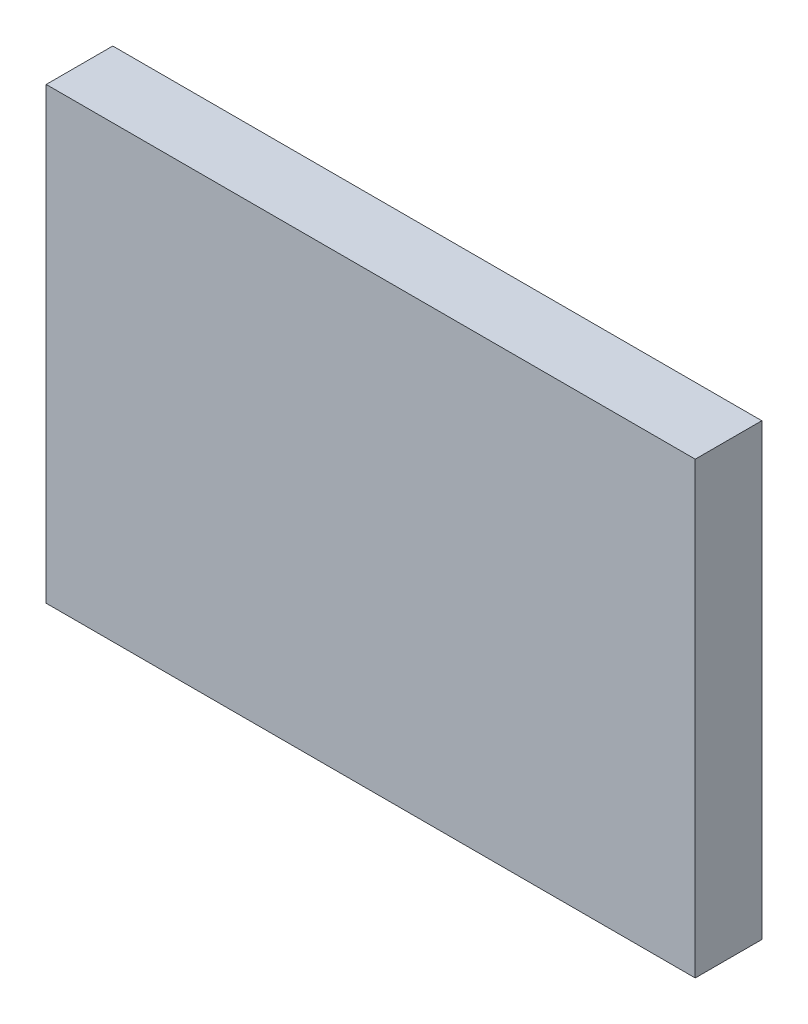
SolidWorks part; units mm, degrees
ref_plane "Front Plane" through (0, 0, 0) normal (0, 0, 1) x (1, 0, 0)
ref_plane "Top Plane" through (0, 0, 0) normal (0, 1, 0) x (1, 0, 0)
ref_plane "Right Plane" through (0, 0, 0) normal (1, 0, 0) x (0, 0, -1)
sketch "Sketch1" plane through (0, 0, 0) normal (0, 0, 1) x (1, 0, 0)
  line L1 (195, -135) -> (-195, -135)
  line L2 (195, -135) -> (195, 135)
  line L3 (195, 135) -> (-195, 135)
  line L4 (-195, -135) -> (-195, 135)
  line L5 (195, -135) -> (-195, 135) construction
  line L6 (195, 135) -> (-195, -135) construction
  point P0 (0, 0)
  dimension "D1" = 390
  dimension "D2" = 270
extrude "Boss-Extrude1" add sketch "Sketch1" along normal blind 40
